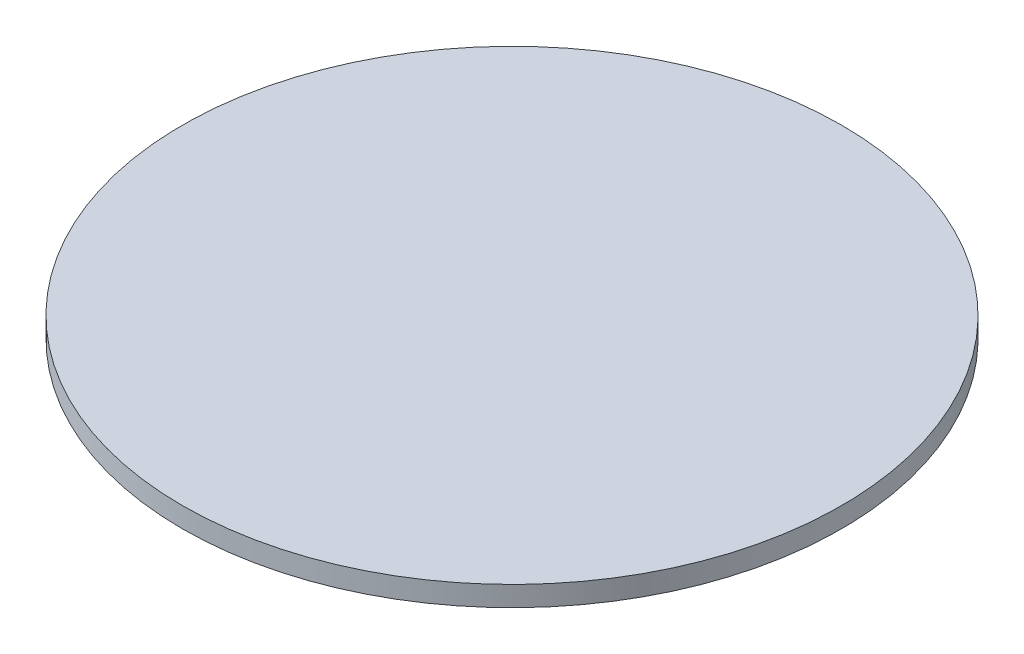
SolidWorks part; units mm, degrees
material "Glass"
ref_plane "Front Plane" through (0, 0, 0) normal (0, 0, 1) x (1, 0, 0)
ref_plane "Top Plane" through (0, 0, 0) normal (0, 1, 0) x (1, 0, 0)
ref_plane "Right Plane" through (0, 0, 0) normal (1, 0, 0) x (0, 0, -1)
sketch "Sketch1" plane through (0, 0, 0) normal (0, 1, 0) x (1, 0, 0)
  circle A0 centre (0, 0) radius 18
  dimension "D1" = 36
extrude "Boss-Extrude1" add sketch "Sketch1" along normal blind 1.1
